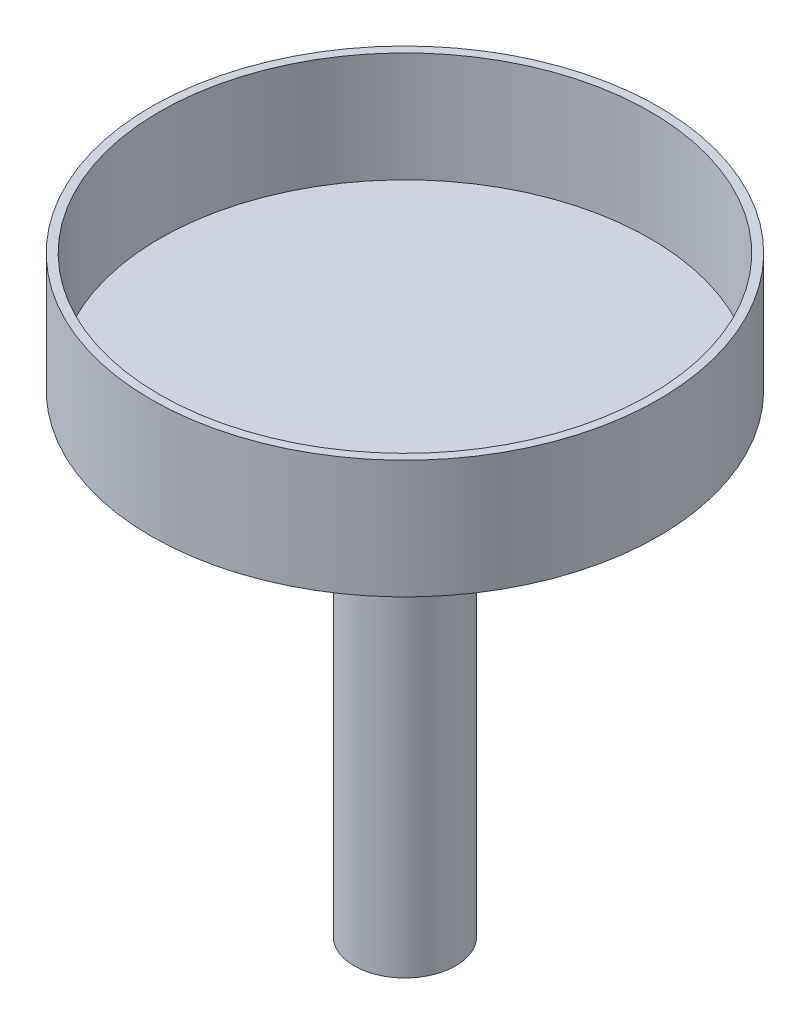
SolidWorks part; units mm, degrees
ref_plane "Front Plane" through (0, 0, 0) normal (0, 0, 1) x (1, 0, 0)
ref_plane "Top Plane" through (0, 0, 0) normal (0, 1, 0) x (1, 0, 0)
ref_plane "Right Plane" through (0, 0, 0) normal (1, 0, 0) x (0, 0, -1)
sketch "Sketch1" plane through (0, 0, 0) normal (0, 0, 1) x (1, 0, 0)
  line L0 (0, 21.6797) -> (0, -27.7734) construction
  line L1 (30, -280) -> (30, 0)
  line L2 (30, 0) -> (150, 0)
  line L3 (150, 0) -> (150, 70)
  line L4 (150, 70) -> (145, 70)
  line L5 (145, 70) -> (145, 5)
  line L6 (145, 5) -> (0, 5)
  line L7 (0, 5) -> (0, -280)
  line L8 (0, -280) -> (30, -280)
  dimension "D1" = 5
  dimension "D2" = 5
  dimension "D3" = 70
  dimension "D4" = 350
  dimension "D5" = 30
  dimension "D6" = 150
revolve "Revolve1" add sketch "Sketch1" angle 360 about L0
